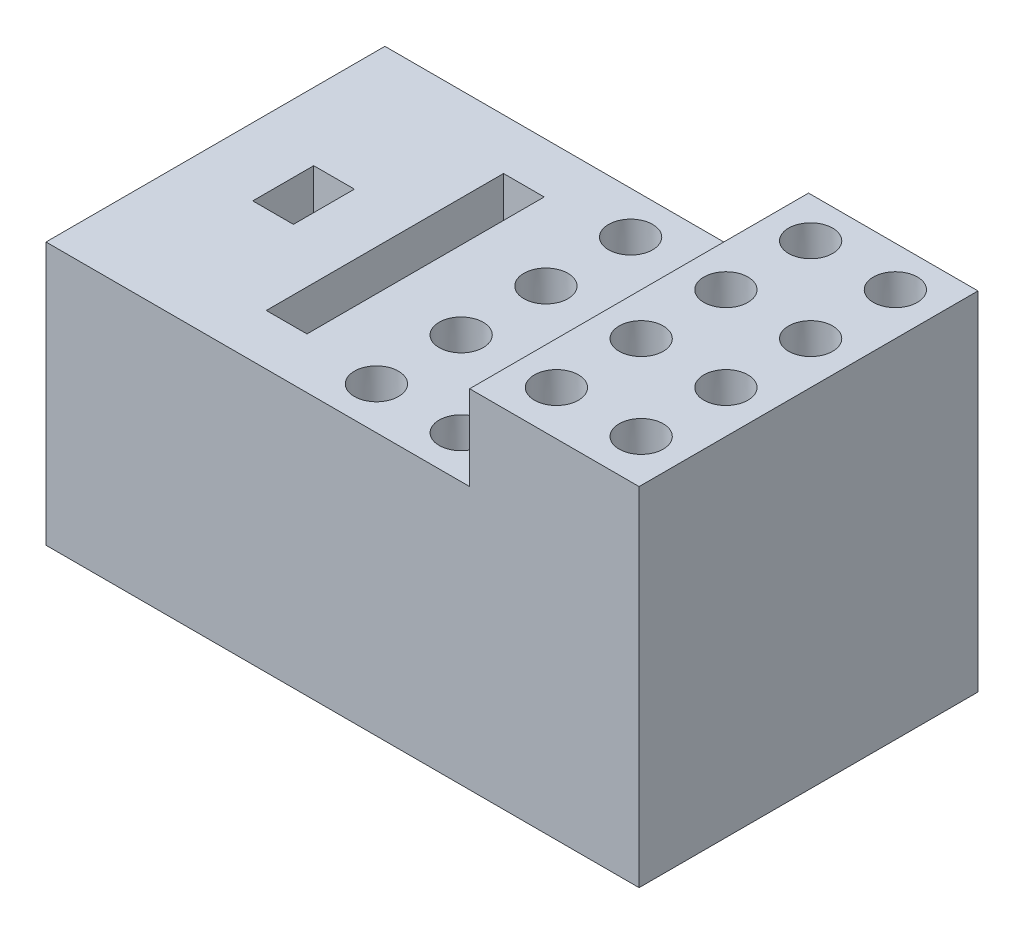
SolidWorks part; units mm, degrees
ref_plane "Front Plane" through (0, 0, 0) normal (0, 0, 1) x (1, 0, 0)
ref_plane "Top Plane" through (0, 0, 0) normal (0, 1, 0) x (1, 0, 0)
ref_plane "Right Plane" through (0, 0, 0) normal (1, 0, 0) x (0, 0, -1)
sketch "Sketch1" plane through (0, 0, 0) normal (0, 0, 1) x (1, 0, 0)
  line L0 (0, 0) -> (175, 0)
  line L1 (175, 0) -> (175, 102.5)
  line L2 (175, 102.5) -> (125, 102.5)
  line L3 (125, 102.5) -> (125, 77.5)
  line L4 (125, 77.5) -> (0, 77.5)
  line L5 (0, 77.5) -> (0, 0)
  dimension "D1" = 77.5
  dimension "D2" = 102.5
  dimension "D3" = 175
  dimension "D4" = 125
extrude "block" add sketch "Sketch1" along normal blind 100
sketch "Sketch2" plane through (0, 77.5, 0) normal (0, 1, 0) x (1, 0, 0)
  line L0 (125, 0) -> (0, 0) construction
  line L1 (0, -100) -> (0, 0) construction
  line L2 (85, -12.5) -> (110, -12.5) construction
  circle A0 centre (85, -12.5) radius 6.5
  circle A1 centre (110, -12.5) radius 6.5
  circle A2 centre (110, -37.5) radius 6.5
  circle A3 centre (110, -62.5) radius 6.5
  circle A4 centre (110, -87.5) radius 6.5
  circle A5 centre (85, -37.5) radius 6.5
  circle A6 centre (85, -62.5) radius 6.5
  circle A7 centre (85, -87.5) radius 6.5
  dimension "D1" = 13
  dimension "D2" = 12.5
  dimension "D3" = 85
  dimension "D6" = 25
  dimension "D4" = 2
  dimension "D5" = 4
extrude "sharpie" cut sketch "Sketch2" against normal blind 75 draft 1.3
sketch "Sketch3" plane through (0, 102.5, 0) normal (0, 1, 0) x (1, 0, 0)
  line L0 (125, -100) -> (125, 0) construction
  circle A0 centre (137.5, -11.8845) radius 6.5
  circle A1 centre (162.5, -11.8845) radius 6.5
  circle A2 centre (162.5, -36.8845) radius 6.5
  circle A3 centre (162.5, -61.8845) radius 6.5
  circle A4 centre (162.5, -86.8845) radius 6.5
  circle A5 centre (137.5, -36.8845) radius 6.5
  circle A6 centre (137.5, -61.8845) radius 6.5
  circle A7 centre (137.5, -86.8845) radius 6.5
  dimension "D1" = 13
  dimension "D4" = 12.5
  dimension "D2" = 2
  dimension "D3" = 4
extrude "prec screwdriver" cut sketch "Sketch3" against normal blind 100 draft 1
sketch "Sketch4" plane through (0, 77.5, 0) normal (0, 1, 0) x (1, 0, 0)
  line L0 (0, -50) -> (100, -50) construction
  line L8 (0, -50) -> (0, 0) construction
  line L9 (0, -100) -> (0, 0) construction
  line L10 (0, -50) -> (0, -100) construction
  line L14 (62, -85) -> (50, -85)
  line L15 (62, -85) -> (62, -15)
  line L16 (62, -15) -> (50, -15)
  line L17 (50, -85) -> (50, -15)
  line L18 (62, -85) -> (50, -15) construction
  line L19 (62, -15) -> (50, -85) construction
  point P0 (56, -50)
  dimension "D1" = 12
  dimension "D2" = 70
  dimension "D3" = 50
extrude "needle nose" cut sketch "Sketch4" against normal blind 75 draft 3
sketch "Sketch6" plane through (0, 77.5, 0) normal (0, 1, 0) x (1, 0, 0)
  line L0 (-200000, -50) -> (200100, -50) construction
  line L1 (32, -59) -> (20, -59)
  line L2 (32, -59) -> (32, -41)
  line L3 (32, -41) -> (20, -41)
  line L4 (20, -59) -> (20, -41)
  line L5 (32, -59) -> (20, -41) construction
  line L6 (32, -41) -> (20, -59) construction
  line L7 (0, -50) -> (0, -100) construction
  point P0 (26, -50)
  dimension "D1" = 12
  dimension "D2" = 18
  dimension "D3" = 20
extrude "scissor" cut sketch "Sketch6" against normal blind 75 draft 3
shell "Shell2" [suppressed] thickness 1
